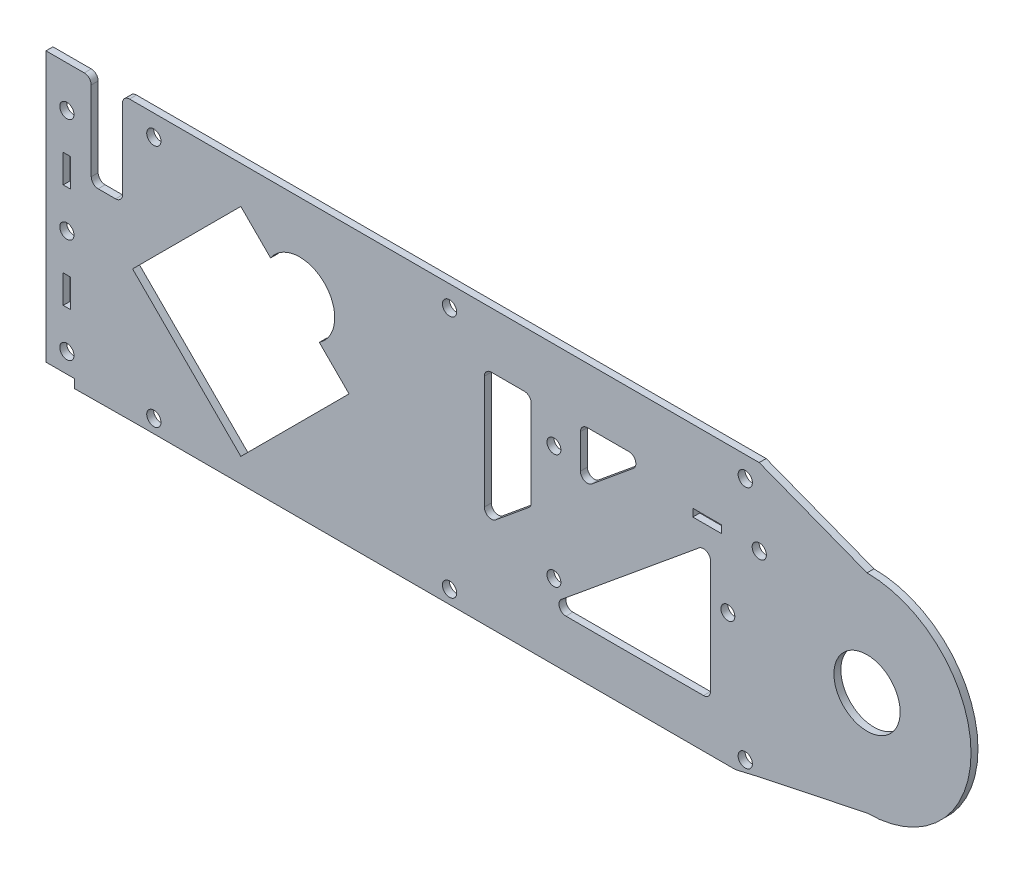
SolidWorks part; units mm, degrees
ref_plane "前视基准面" through (0, 0, 0) normal (0, 0, 1) x (1, 0, 0)
ref_plane "上视基准面" through (0, 0, 0) normal (0, 1, 0) x (1, 0, 0)
ref_plane "右视基准面" through (0, 0, 0) normal (1, 0, 0) x (0, 0, -1)
sketch "草图1" plane through (0, 0, 0) normal (0, 0, 1) x (1, 0, 0)
  line L0 (0.5429, 31.9043) -> (0.5429, 27.8043)
  line L1 (0.5429, 18.7543) -> (0.5429, 10.9543) construction
  line L2 (-0.5071, 10.8043) -> (1.5929, 10.8043)
  line L3 (-0.5071, 10.8043) -> (-0.5071, 18.9043)
  line L4 (-0.5071, 18.9043) -> (1.5929, 18.9043)
  line L5 (1.5929, 10.8043) -> (1.5929, 18.9043)
  line L6 (-0.5071, 10.8043) -> (1.5929, 18.9043) construction
  line L7 (-0.5071, 18.9043) -> (1.5929, 10.8043) construction
  line L12 (0.5429, -0.1457) -> (-5.3571, -0.1457) construction
  line L18 (50.5429, -0.1457) -> (97.8433, -0.1457) construction
  line L19 (50.5429, -0.1457) -> (230.5429, -0.1457) construction
  line L20 (200.6429, -0.1457) -> (200.6429, 38.1043) construction
  line L42 (230.5429, -30.0457) -> (199.5561, -36.5559)
  line L47 (2.6929, -38.2957) -> (-5.4571, -38.2957)
  line L49 (-5.4571, 41.7043) -> (7.5429, 41.7043)
  line L54 (199.5429, 41.7043) -> (230.5429, 29.7543)
  line L55 (7.5429, 41.7043) -> (7.5429, 14.8543)
  line L57 (7.5429, 14.8543) -> (16.5429, 14.8543)
  line L59 (-5.4571, 41.7043) -> (261.5429, 41.7043) construction
  line L60 (16.5429, 41.7043) -> (199.5429, 41.7043)
  line L61 (16.5429, 41.7043) -> (16.5429, 14.8543)
  line L62 (50.5429, 13.8543) -> (59.0992, 22.4106) construction
  line L63 (64.5429, -0.1457) -> (73.0992, 8.4106) construction
  line L64 (59.0992, 22.4106) -> (50.5429, 30.967)
  line L65 (19.4302, -0.1457) -> (50.5429, 30.967)
  line L66 (19.4302, -0.1457) -> (50.5429, -31.2584)
  line L67 (50.5429, -31.2584) -> (81.6556, -0.1457)
  line L68 (50.5429, 30.967) -> (81.6556, -0.1457) construction
  line L69 (19.4302, -0.1457) -> (81.6556, -0.1457) construction
  line L70 (50.5429, -31.2584) -> (50.5429, 30.967) construction
  line L71 (73.0992, 8.4106) -> (81.6556, -0.1457)
  line L72 (0.5429, -0.1457) -> (50.5429, -0.1457) construction
  line L73 (-0.5071, -19.1957) -> (1.5929, -11.0957) construction
  line L74 (-0.5071, -11.0957) -> (1.5929, -19.1957) construction
  line L75 (0.5429, -19.0457) -> (0.5429, -11.2457) construction
  line L76 (1.5929, -11.0957) -> (1.5929, -19.1957)
  line L77 (-0.5071, -19.1957) -> (1.5929, -19.1957)
  line L78 (-0.5071, -11.0957) -> (-0.5071, -19.1957)
  line L79 (-0.5071, -11.0957) -> (1.5929, -11.0957)
  line L80 (199.5561, -36.5559) -> (192.7469, -38.1457)
  line L81 (192.7469, -38.1457) -> (21.3658, -38.1457)
  line L82 (21.3658, -38.1457) -> (2.6929, -38.2957)
  line L83 (-5.4571, 41.7043) -> (-5.4571, -35.8026)
  line L84 (-5.4571, -35.8026) -> (2.6929, -35.8026)
  line L85 (2.6929, -35.8026) -> (2.6929, -38.2957)
  circle A0 centre (0.5429, 29.8543) radius 2.05
  circle A1 centre (0.5429, -0.1457) radius 2.05
  circle A2 centre (0.5429, -30.1457) radius 2.05
  circle A15 centre (230.5429, -0.1457) radius 9.525
  circle A16 centre (230.5429, -0.1457) radius 29.9 construction
  arc A17 (230.5429, -30.0457) -> (230.5429, 29.7543) centre (230.5429, -0.1457) ccw
  arc A19 (59.0992, 22.4106) -> (73.0992, 8.4106) centre (67.4545, 16.7659) cw
  point P6 (0.5429, 14.8543)
  point P25 (50.5429, -0.1457)
  point P67 (0.5429, -15.1457)
  dimension "D3" = 44
  dimension "D4" = 44
  dimension "D13" = 19.05
  dimension "D1" = 8.1
  dimension "D2" = 2.1
  dimension "D5" = 50
  dimension "D7" = 15
  dimension "D8" = 60
  dimension "D9" = 30
  dimension "D14" = 180
extrude "凸台-拉伸1" add sketch "草图1" along normal blind 2
sketch "草图3" plane through (0, 0, 2) normal (0, 0, 1) x (1, 0, 0)
  line L0 (16.5429, 41.7043) -> (199.5429, 41.7043) construction
  line L1 (16.5429, 41.7043) -> (16.5429, 14.8543) construction
  line L2 (148.1533, 25.7043) -> (148.1533, 9.6322)
  line L3 (110.5429, -34.2957) -> (195.5429, 35.7043) construction
  line L4 (195.5429, 35.7043) -> (195.5429, -34.2957) construction
  line L5 (195.5429, -34.2957) -> (110.5429, -34.2957) construction
  line L6 (185.5429, -24.2957) -> (138.4162, -24.2957)
  line L7 (138.4162, -24.2957) -> (185.5429, 14.5145)
  line L8 (185.5429, 14.5145) -> (185.5429, -24.2957)
  line L9 (110.5429, -34.2957) -> (110.5429, 35.7043) construction
  line L10 (110.5429, 35.7043) -> (195.5429, 35.7043) construction
  line L11 (120.5429, 25.7043) -> (167.6695, 25.7043) construction
  line L12 (120.5429, -13.1059) -> (167.6695, 25.7043) construction
  line L13 (120.5429, -13.1059) -> (120.5429, 25.7043)
  line L15 (134.0149, 25.7043) -> (134.0149, -2.0113)
  line L17 (134.0149, 25.7043) -> (120.5429, 25.7043)
  line L19 (134.0149, -2.0113) -> (120.5429, -13.1059)
  line L21 (148.1533, 25.7043) -> (167.6695, 25.7043)
  line L22 (167.6695, 25.7043) -> (148.1533, 9.6322)
  line L23 (199.574, 19.7043) -> (184.574, 19.7043) construction
  line L24 (16.5429, 41.7043) -> (199.5429, 41.7043) construction
  line L25 (188.674, 20.8043) -> (180.474, 20.8043)
  line L26 (188.674, 20.8043) -> (188.674, 18.6043)
  line L27 (188.674, 18.6043) -> (180.474, 18.6043)
  line L28 (180.474, 20.8043) -> (180.474, 18.6043)
  line L29 (188.674, 20.8043) -> (180.474, 18.6043) construction
  line L30 (188.674, 18.6043) -> (180.474, 20.8043) construction
  circle A0 centre (25.5429, 35.7043) radius 2.05
  circle A1 centre (110.5429, 35.7043) radius 2.05
  circle A2 centre (195.5429, 35.7043) radius 2.05
  circle A3 centre (110.5429, -34.2957) radius 2.05
  circle A4 centre (195.5429, -34.2957) radius 2.05
  circle A5 centre (25.5429, -34.2957) radius 2.05
  circle A6 centre (190.5429, -0.1457) radius 2
  circle A7 centre (140.5429, 16.3543) radius 2
  circle A8 centre (140.5429, -16.6457) radius 2
  circle A9 centre (230.5429, -0.1457) radius 2 construction
  circle A10 centre (199.574, 19.7043) radius 2.05
  dimension "D1" = 6
  dimension "D7" = 15
  dimension "D2" = 9
  dimension "D8" = 2.2
  dimension "D9" = 8.2
  dimension "D10" = 22
  dimension "D5" = 10
  dimension "D6" = 10
  dimension "D3" = 3
  dimension "D4" = 2
fillet "圆角1" radius 2 4 edges at (16.5429, 41.7043, 1) (7.5429, 41.7043, 1) (7.5429, 14.8543, 1) (16.5429, 14.8543, 1)
extrude "切除-拉伸1" cut sketch "草图3" against normal blind 2
fillet "圆角2" radius 2 10 edges at (134.0149, -2.0113, 1) (134.0149, 25.7043, 1) (120.5429, 25.7043, 1) (120.5429, -13.1059, 1) (185.5429, -24.2957, 1) (185.5429, 14.5145, 1) (138.4162, -24.2957, 1) (148.1533, 9.6322, 1) (148.1533, 25.7043, 1) (167.6695, 25.7043, 1)
